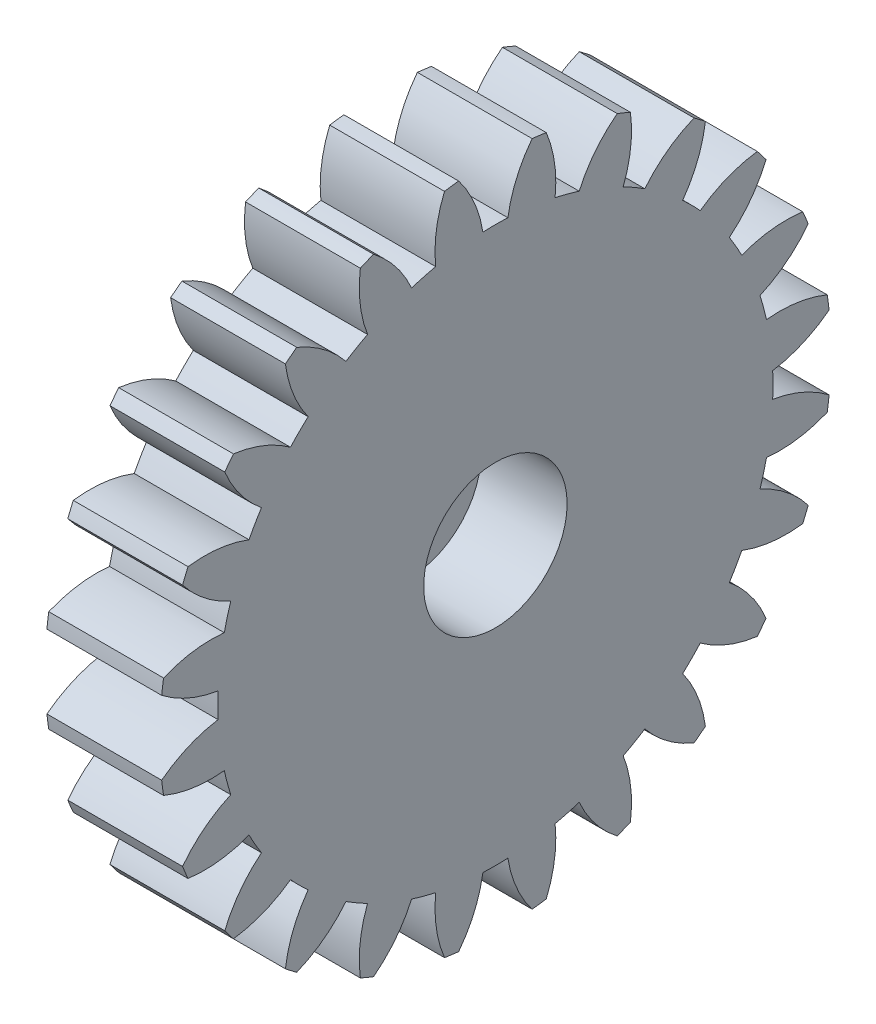
SolidWorks part; units mm, degrees
ref_plane "Plane1" through (0, 0, 0) normal (0, 0, 1) x (1, 0, 0)
ref_plane "Plane2" through (0, 0, 0) normal (0, 1, 0) x (1, 0, 0)
ref_plane "Plane3" through (0, 0, 0) normal (1, 0, 0) x (0, 0, -1)
other "Configuration Table"
sketch "HoldingSke" plane through (0, 0, 0) normal (0, 1, 0) x (1, 0, 0)
  line L0 (0, 0) -> (1.0151, -0.4519)
  line L1 (-15, 0) -> (100, 0) construction
  line L2 (0, 0) -> (-2.1039, 2.3779)
  line L3 (0, 0) -> (-11.863, 4.5341)
  line L4 (0, 0) -> (7.8894, 3.5126)
  line L5 (0, 0) -> (-46.8476, -17.4728)
  line L6 (0, 0) -> (-3.3159, -2.2372)
  line L7 (-2.1039, 2.3779) -> (8.6586, 51.2059)
  line L8 (-76.2, 54.61) -> (-75.9, 54.61)
  line L9 (-71.009, 38.7566) -> (-53.1078, 45.2721)
  line L10 (-76.2, 71.12) -> (104.1128, 71.12)
  line L11 (0, 0) -> (-4, 0)
  line L12 (-76.2, 101.6) -> (-76.166, 101.6)
  line L13 (24.9733, 27.94) -> (52.9518, 28.4284)
  line L14 (24.9733, 27.94) -> (24.9743, 27.94)
  line L15 (24.9733, 27.94) -> (100.4006, 29.5858)
  line L16 (-63.627, -0.9) -> (-12.827, -0.9)
  circle A0 centre (0, 0) radius 1
  circle A1 centre (0, 0) radius 9.674
  circle A2 centre (0, 0) radius 37.5
  circle A3 centre (0, 0) radius 1
  dimension "MHD" = 19.348
  dimension "Hub_dia" = 75
  dimension "Bore" = 2
  dimension "MBD" = 2
  dimension "Num_teeth" = 24
  dimension "Pitch" = 1.1111
  dimension "Overall_len" = 50
  dimension "Show_teeth" = 24
  dimension "Thickness" = 4
  dimension "OAL" = 50.0001
  dimension "T_dim" = 0.3
  dimension "Ap" = 20
  dimension "H" = 19.05
  dimension "Pitch_radius" = 180.3128
  dimension "Width" = 4
  dimension "Backlash" = 0.034
  dimension "Addendum_fac" = 1
  dimension "Dedendum_fac" = 1.25
  dimension "Clearance_fac" = 0.25
  dimension "Dedendum_add" = 0.001
  dimension "Module" = 0.9
sketch "BasProSke" plane through (0, 0, 0) normal (0, 1, 0) x (1, 0, 0)
  line L0 (-10, 0) -> (60, 0) construction
  line L1 (0, 0) -> (0, 11.7)
  line L2 (0, 0) -> (4, 0)
  line L3 (4, 0) -> (4, 11.7)
  line L4 (4, 11.7) -> (0, 11.7)
  dimension "Thickness" = 4
  dimension "Diameter" = 23.4
revolve "Base-Revolve" add sketch "BasProSke" angle 360 about L0
sketch "TooCutSke" plane through (0, 0, 0) normal (1, 0, 0) x (0, 0, -1)
  line L1 (0, 0) -> (0, 107) construction
  line L2 (0, 0) -> (-0.7658, 10.7728) construction
  line L3 (0, 0) -> (-2.8143, 21.3768) construction
  line L4 (-0.7658, 10.7728) -> (-1.4072, 10.6884) construction
  arc A0 (0.4348, 9.6642) -> (-0.4348, 9.6642) centre (0, 0) ccw
  arc A1 (1.2983, 11.6533) -> (-1.2983, 11.6533) centre (0, 0) ccw
  circle A2 centre (0, 0) radius 10.8 construction
  circle A3 centre (0, 0) radius 10.1487 construction
  arc A4 (-0.4348, 9.6642) -> (-1.2983, 11.6533) centre (-4.7024, 8.9935) ccw
  arc A5 (1.2983, 11.6533) -> (0.4348, 9.6642) centre (4.7024, 8.9935) ccw
  dimension "Root_dia" = 19.348
  dimension "Overcut_dia" = 23.4508
  dimension "Pitch_dia" = 21.6
  dimension "Base_dia" = 20.2974
  dimension "Flank_rad" = 4.32
  dimension "Half_ang" = 7.5
  dimension "Half_CT" = 0.6469
extrude "ToothCut" cut sketch "TooCutSke" along normal through all
fillet "Breaks" [suppressed] radius 0.018
fillet "RootFillets" [suppressed] radius 0.226
pattern_circular "TeethCuts" count 24 every 15 about axis through (-10, 0, 0) along (1, 0, 0) of "ToothCut", "RootFillets", "Breaks"
sketch "HubNeaOneSke" plane through (0, 0, 0) normal (-1, 0, 0) x (0, 0, 1)
  circle A0 centre (0, 0) radius 9.674
  dimension "Diameter" = 19.348
extrude "HubNearOne" [suppressed] add sketch "HubNeaOneSke" along normal blind 46.0001
sketch "HubNeaBotSke" plane through (0, 0, 0) normal (-1, 0, 0) x (0, 0, 1)
  circle A0 centre (0, 0) radius 9.674
  dimension "Diameter" = 19.348
extrude "HubNearBoth" [suppressed] add sketch "HubNeaBotSke" along normal blind 23
ref_plane "FarPln" through (4, 0, 0) normal (1, 0, 0) x (0, 0, -1)
sketch "HubFarSke" plane through (4, 0, 0) normal (1, 0, 0) x (0, 0, -1)
  circle A0 centre (0, 0) radius 9.674
  dimension "Diameter" = 19.348
extrude "HubFar" [suppressed] add sketch "HubFarSke" along normal blind 23
sketch "BorSke" plane through (0, 0, 0) normal (1, 0, 0) x (0, 0, -1)
  circle A0 centre (0, 0) radius 1
  dimension "Diameter" = 2
extrude "Bore" cut sketch "BorSke" along normal mid plane 100.0001
sketch "KeySke" plane through (0, 0, 0) normal (1, 0, 0) x (0, 0, -1)
  line L0 (-0.4, 0) -> (-0.4, 1.3)
  line L1 (-0.4, 1.3) -> (0.4, 1.3)
  line L2 (0.4, 1.3) -> (0.4, 0)
  line L3 (0, 0) -> (0, 34) construction
  line L4 (-0.4, 0) -> (0.4, 0)
  dimension "Offset" = 1.3
  dimension "Width" = 0.8
extrude "Keyway" [suppressed] cut sketch "KeySke" along normal mid plane 100.0001
pattern_circular "Keyway2" [suppressed] count 2 every 90 about axis through (-10, 0, 0) along (1, 0, 0)
sketch "Sketch1" plane through (4, 0, 0) normal (1, 0, 0) x (0, 0, -1)
  circle A0 centre (0, 0) radius 2.5
extrude "Cut-Extrude1" cut sketch "Sketch1" against normal blind 3
equation "' \"Module@HoldingSke\" = 6.35"
equation "' \"Num_teeth@HoldingSke\" = 12"
equation "' \"Ap@HoldingSke\" =  20"
equation "' \"Ap@HoldingSke\" = 20"
equation "' \"Width@HoldingSke\" = 0.5 * 25.4"
equation "' \"Hub_dia@HoldingSke\"= 1 * 25.4"
equation "' \"Hub_dia@HoldingSke\" = 1 * 25.4"
equation "' \"Overall_len@HoldingSke\" = 1.0 * 25.4"
equation "' \"Bore@HoldingSke\" = 0.75 * 25.4"
equation "' \"T_dim@HoldingSke\" = 0.1 * 25.4"
equation "' \"Width@KeySke\" = 0.25 * 25.4"
equation "' \"Show_teeth@HoldingSke\" = 13"
equation "' \"Backlash@HoldingSke\" = 0.009 * 25.4"
equation "' \"Addendum_fac@HoldingSke\" = 1.0"
equation "' \"Dedendum_fac@HoldingSke\" = 1.25"
equation "' \"Dedendum_add@HoldingSke\" = 0.00005 * 25.4"
equation "' \"Clearance_fac@HoldingSke\" = 0.25"
equation "\"Pitch@HoldingSke\" = 1 / \"Module@HoldingSke\""
equation "\"Overcut_dia@TooCutSke\" = (\"Num_teeth@HoldingSke\" + 2 * \"Addendum_fac@HoldingSke\") / \"Pitch@HoldingSke\" + 0.002 * 25.4"
equation "\"Pitch_dia@TooCutSke\" = \"Num_teeth@HoldingSke\" / \"Pitch@HoldingSke\""
equation "\"Base_dia@TooCutSke\" = \"Num_teeth@HoldingSke\" / \"Pitch@HoldingSke\" * cos((\"Ap@HoldingSke\"  * 3.14159265 / 180))"
equation "\"Root_dia@TooCutSke\" = (\"Num_teeth@HoldingSke\" + 2) / \"Pitch@HoldingSke\" - 2 * (\"Addendum_fac@HoldingSke\" + \"Dedendum_fac@HoldingSke\") / \"Pitch@HoldingSke\" - \"Dedendum_add@HoldingSke\" * 2"
equation "\"Half_ang@TooCutSke\" = 180 / \"Num_teeth@HoldingSke\""
equation "\"Half_CT@TooCutSke\" = \"Num_teeth@HoldingSke\" / \"Pitch@HoldingSke\" * sin((3.14159265 / 2 / \"Num_teeth@HoldingSke\")) / 2 - 7 * \"Backlash@HoldingSke\" / 4"
equation "\"Flank_rad@TooCutSke\" = \"Num_teeth@HoldingSke\" / \"Pitch@HoldingSke\" / 5"
equation "\"Radius@RootFillets\" = \"Clearance_fac@HoldingSke\" / \"Pitch@HoldingSke\" + \"Dedendum_add@HoldingSke\""
equation "\"Break_rad@Breaks\" = 0.02 / \"Pitch@HoldingSke\""
equation "\"Thickness@HoldingSke\" = \"Width@HoldingSke\""
equation "\"OAL@HoldingSke\" = \"Thickness@HoldingSke\""
equation "\"MHD@HoldingSke\" = (\"Num_teeth@HoldingSke\" + 2) / \"Pitch@HoldingSke\" - 2 * (\"Addendum_fac@HoldingSke\" + \"Dedendum_fac@HoldingSke\")  / \"Pitch@HoldingSke\" - \"Dedendum_add@HoldingSke\" * 2"
equation "\"MBD@HoldingSke\" = (\"Num_teeth@HoldingSke\" + 2) / \"Pitch@HoldingSke\" - 2 * (\"Addendum_fac@HoldingSke\" + \"Dedendum_fac@HoldingSke\")  / \"Pitch@HoldingSke\" - \"Dedendum_add@HoldingSke\" * 2 - 0.002 * 25.4"
equation "\"MHD@HoldingSke\" = ((sgn( \"MHD@HoldingSke\" - \"Hub_dia@HoldingSke\" )-1)*( \"MHD@HoldingSke\" - \"Hub_dia@HoldingSke\" ))/-2+ \"Hub_dia@HoldingSke\""
equation "\"MBD@HoldingSke\" = ((sgn( \"MBD@HoldingSke\" - \"Bore@HoldingSke\" )-1)*( \"MBD@HoldingSke\" - \"Bore@HoldingSke\" ))/-2+ \"Bore@HoldingSke\""
equation "\"OAL@HoldingSke\" = ((sgn( \"OAL@HoldingSke\" - \"Overall_len@HoldingSke\" )+1)*( \"OAL@HoldingSke\" - \"Overall_len@HoldingSke\" ))/2 + \"Overall_len@HoldingSke\" + 0.000002 * 25.4"
equation "\"Num_teeth@TeethCuts\" = int( \"Show_teeth@HoldingSke\" ) + 1"
equation "\"Num_teeth@TeethCuts\" = ((sgn( \"Num_teeth@TeethCuts\" - \"Num_teeth@HoldingSke\" )-1)*( \"Num_teeth@TeethCuts\" - \"Num_teeth@HoldingSke\" ))/-2+ \"Num_teeth@HoldingSke\""
equation "\"Num_teeth@TeethCuts\" = ((sgn( \"Num_teeth@TeethCuts\" - 2.0)+1)*( \"Num_teeth@TeethCuts\" - 2.0))/2 +2.0"
equation "\"Angle@TeethCuts\" = 360.0 / \"Num_teeth@HoldingSke\""
equation "\"Diameter@BasProSke\" = (\"Num_teeth@HoldingSke\" + 2 * \"Addendum_fac@HoldingSke\") / \"Pitch@HoldingSke\""
equation "\"Thickness@BasProSke\"  = \"Thickness@HoldingSke\""
equation "' \"Fillet_rad@BasProSke\" =  \"Thickness@HoldingSke\" * 0.05"
equation "' \"Fillet_rad@BasProSke\" = \"Thickness@HoldingSke\" * 0.05"
equation "\"MHD@HoldingSke\" = ((sgn( \"MHD@HoldingSke\" - \"Root_dia@TooCutSke\" )-1)*( \"MHD@HoldingSke\" - \"Root_dia@TooCutSke\" ))/-2+ \"Root_dia@TooCutSke\""
equation "\"Diameter@HubNeaOneSke\" = \"MHD@HoldingSke\""
equation "\"Length@HubNearOne\" = \"OAL@HoldingSke\" - \"Thickness@BasProSke\""
equation "\"Diameter@HubNeaBotSke\" = \"MHD@HoldingSke\""
equation "\"Length@HubNearBoth\" = ( \"OAL@HoldingSke\" - \"Thickness@BasProSke\" ) / 2.0"
equation "\"Thickness@FarPln\" = \"Thickness@BasProSke\""
equation "\"Diameter@HubFarSke\" = \"MHD@HoldingSke\""
equation "\"Length@HubFar\" = ( \"OAL@HoldingSke\" - \"Thickness@BasProSke\" ) / 2.0"
equation "\"Diameter@BorSke\" = \"MBD@HoldingSke\""
equation "\"D1@Bore\" = \"OAL@HoldingSke\" * 2.0"
equation "\"D1@Keyway\" = \"OAL@HoldingSke\" * 2.0"
equation "\"Offset@KeySke\" = \"T_dim@HoldingSke\" + \"MBD@HoldingSke\" / 2.0"
